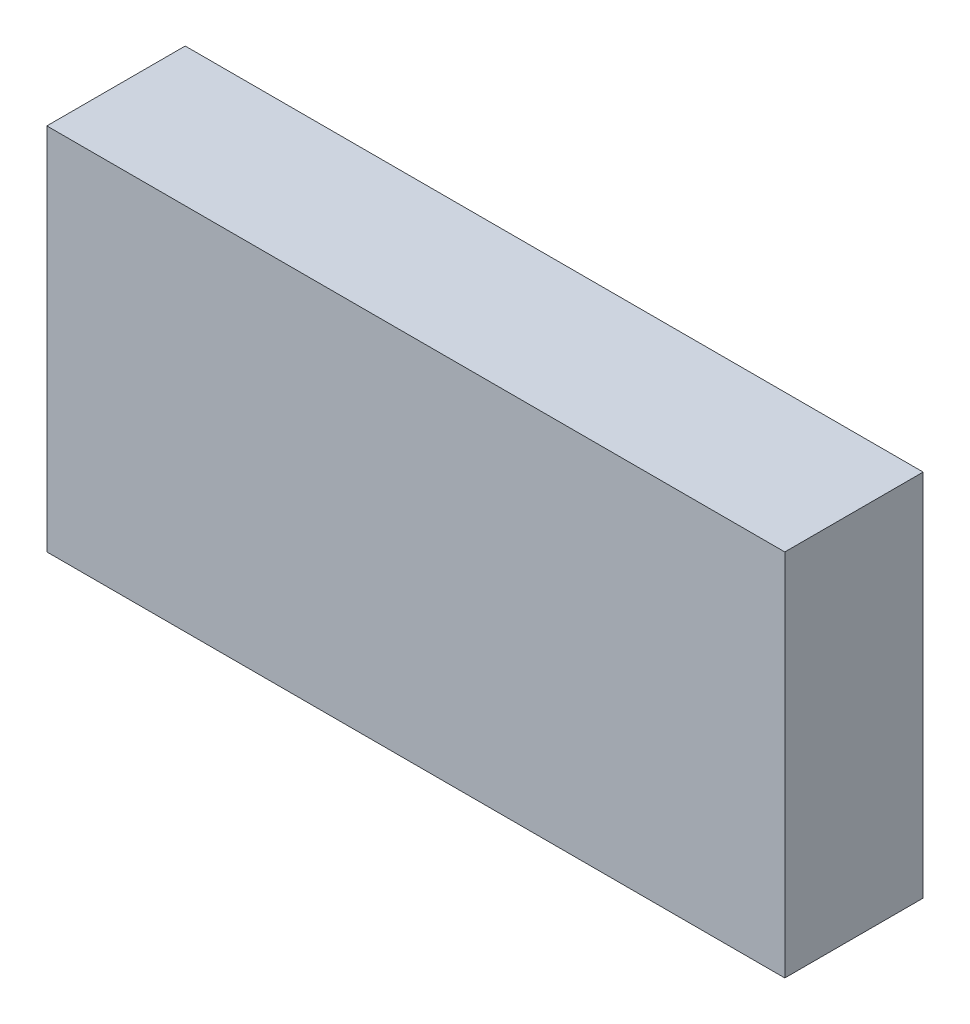
SolidWorks part; units mm, degrees
ref_plane "Front Plane" through (0, 0, 0) normal (0, 0, 1) x (1, 0, 0)
ref_plane "Top Plane" through (0, 0, 0) normal (0, 1, 0) x (1, 0, 0)
ref_plane "Right Plane" through (0, 0, 0) normal (1, 0, 0) x (0, 0, -1)
sketch "Sketch1" plane through (0, 0, 0) normal (0, 0, 1) x (1, 0, 0)
  line L1 (-40, -20) -> (40, -20)
  line L2 (-40, -20) -> (-40, 20)
  line L3 (-40, 20) -> (40, 20)
  line L4 (40, -20) -> (40, 20)
  line L5 (-40, -20) -> (40, 20) construction
  line L6 (-40, 20) -> (40, -20) construction
  point P0 (0, 0)
  dimension "D1" = 40
  dimension "D2" = 80
extrude "Boss-Extrude1" add sketch "Sketch1" along normal blind 15
sketch "Sketch2" plane through (0, 0, 15) normal (0, 0, 1) x (1, 0, 0)
  line L1 (-40, -20) -> (40, -20) construction
  line L2 (0, 0) -> (0, -50000) construction
  circle A0 centre (0, -14) radius 12
  circle A1 centre (27, -14) radius 12
  circle A2 centre (0, -14) radius 11 construction
  circle A3 centre (27, -14) radius 11 construction
  circle A4 centre (-27, -14) radius 12
  circle A5 centre (-27, -14) radius 11 construction
  circle A6 centre (-13.5, -7.4617) radius 5 construction
  circle A7 centre (-13.5, -7.4617) radius 6
  circle A8 centre (13.5, -7.4617) radius 6
  circle A9 centre (13.5, -7.4617) radius 5 construction
  point P7 (0, -26)
  dimension "D1" = 24
  dimension "D2" = 6
  dimension "D3" = 27
  dimension "D4" = 1
  dimension "D5" = 27
  dimension "D6" = 10
  dimension "D7" = 15
  dimension "D8" = 15
  dimension "D9" = 1
